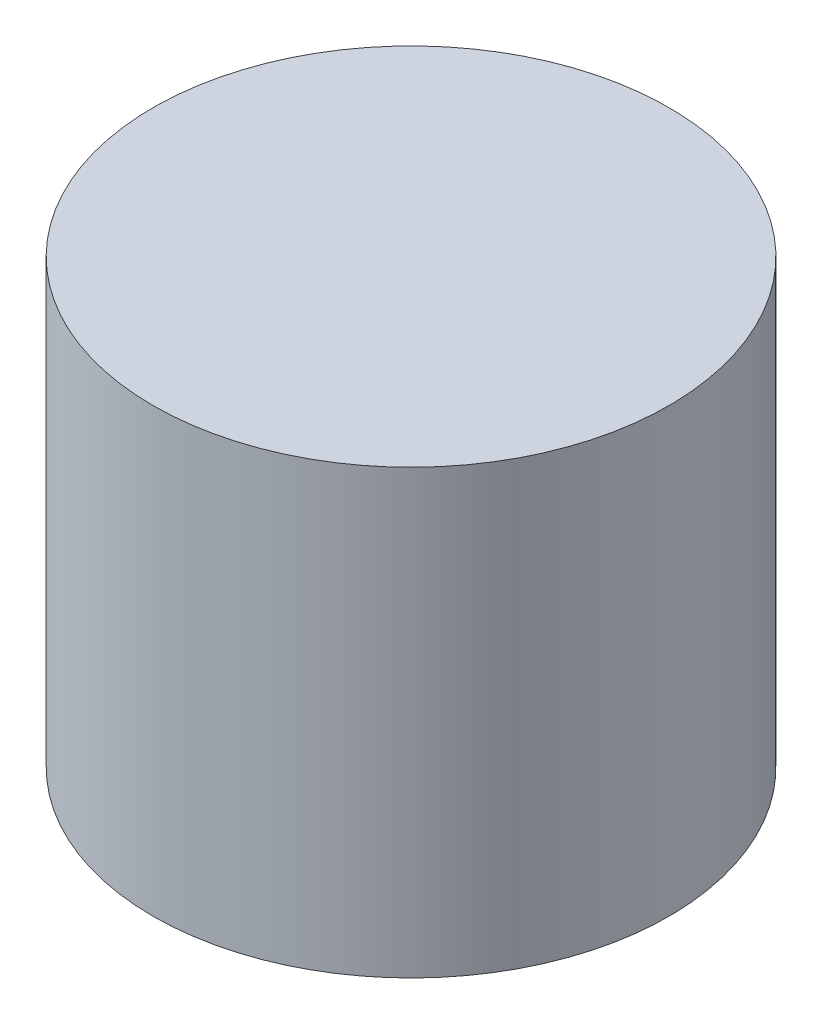
SolidWorks part; units mm, degrees
material "PVC 0.007 Plasticized"
ref_plane "Front Plane" through (0, 0, 0) normal (0, 0, 1) x (1, 0, 0)
ref_plane "Top Plane" through (0, 0, 0) normal (0, 1, 0) x (1, 0, 0)
ref_plane "Right Plane" through (0, 0, 0) normal (1, 0, 0) x (0, 0, -1)
sketch "Sketch1" plane through (0, 0, 0) normal (0, 1, 0) x (1, 0, 0)
  circle A0 centre (0, 0) radius 1.75
  dimension "D1" = 3.5
extrude "Boss-Extrude1" add sketch "Sketch1" along normal blind 3
